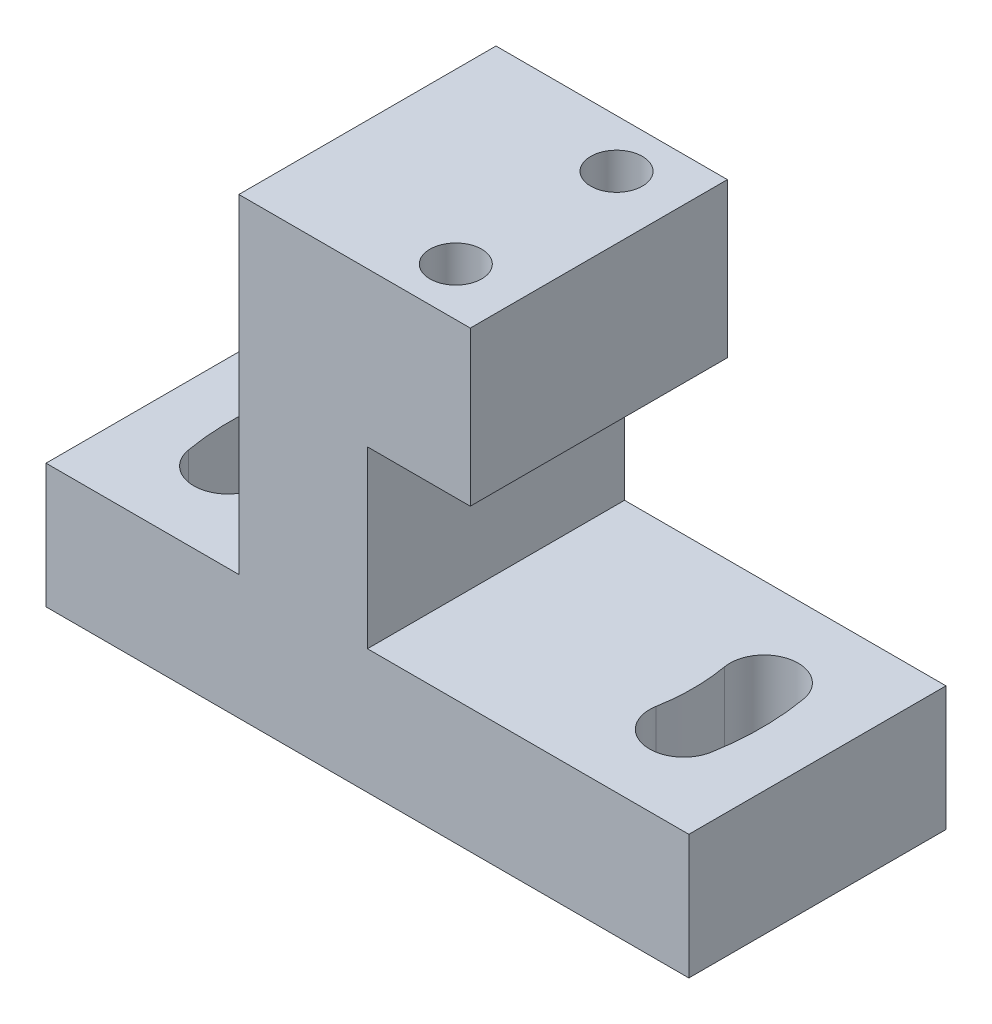
SolidWorks part; units mm, degrees
material "6061 Alloy"
ref_plane "Front Plane" through (0, 0, 0) normal (0, 0, 1) x (1, 0, 0)
ref_plane "Top Plane" through (0, 0, 0) normal (0, 1, 0) x (1, 0, 0)
ref_plane "Right Plane" through (0, 0, 0) normal (1, 0, 0) x (0, 0, -1)
sketch "Sketch1" plane through (0, 0, 0) normal (0, 0, 1) x (1, 0, 0)
  line L2 (-12.7, 44.8056) -> (10.16, 44.8056)
  line L3 (-31.75, 0) -> (31.75, 0)
  line L4 (-31.75, 0) -> (-31.75, 12.2936)
  line L5 (-31.75, 12.2936) -> (-12.7, 12.2936)
  line L6 (31.75, 0) -> (31.75, 12.2936)
  line L8 (-12.7, 12.2936) -> (-12.7, 44.8056)
  line L11 (12.7, 12.2936) -> (31.75, 12.2936)
  line L13 (10.16, 29.5656) -> (0, 29.5656)
  line L14 (10.16, 44.8056) -> (10.16, 29.5656)
  line L15 (12.7, 12.2936) -> (0, 12.2936)
  line L16 (0, 29.5656) -> (0, 12.2936)
  dimension "D1" = 12.7
  dimension "D3" = 63.5
  dimension "D5" = 12.2936
  dimension "D6" = 17.272
  dimension "D7" = 15.24
  dimension "D8" = 10.16
extrude "Extrude1" add sketch "Sketch1" along normal mid plane 25.4
sketch "Sketch2" plane through (0, 12.2936, 0) normal (0, 1, 0) x (-1, 0, 0)
  line L0 (-22.5127, 3.9696) -> (0, 0) construction
  line L1 (0, 0) -> (-22.5127, -3.9696) construction
  line L2 (0, 0) -> (-22.86, 0) construction
  line L3 (0, 22.86) -> (0, -22.86) construction
  circle A0 centre (-22.86, 0) radius 3.3782 construction
  circle A1 centre (0, 0) radius 22.86 construction
  arc A3 (-25.8396, -4.5562) -> (-19.1858, -3.383) centre (-22.5127, -3.9696) ccw
  arc A4 (-19.1858, 3.383) -> (-25.8396, 4.5562) centre (-22.5127, 3.9696) ccw
  arc A5 (-19.1858, 3.383) -> (-19.1858, -3.383) centre (0, 0) ccw
  arc A6 (-25.8396, 4.5562) -> (-25.8396, -4.5562) centre (0, 0) ccw
  dimension "D2" = 45.72
  dimension "D1" = 6.7564
  dimension "D3" = 20
extrude "Arc mounting slot I" cut sketch "Sketch2" against normal through all
mirror "Arc mounting slot II" about plane through (0, 0, 0) normal (1, 0, 0) of "Arc mounting slot I"
hole_wizard "Clamping screw holes" positions "Sketch5" profile "Sketch4" tap size "1/4-20" standard "Ansi Inch"
sketch "Sketch5" plane through (0, 44.8056, 0) normal (0, 1, 0) x (-1, 0, 0)
  line L0 (0, 0) -> (-3.9688, 0) construction
  line L1 (-3.9688, 7.9375) -> (-3.9688, -7.9375) construction
  point P0 (-3.9688, -7.9375)
  point P1 (-3.9688, 7.9375)
  dimension "D1" = 15.875
  dimension "D2" = 3.9688
cosmetic thread "Hole Thread1" parameters "D1"=15.24, "D2"=6.35
cosmetic thread "Hole Thread2" parameters "D1"=15.24, "D2"=6.35
sketch "Sketch4" plane through (3.9688, 44.8056, -7.9375) normal (1, 0, 0) x (0, 0, 1)
  line L0 (0, 0) -> (0, 16.7738)
  line L1 (0, 16.7738) -> (2.5527, 15.24)
  line L2 (2.5527, 15.24) -> (2.5527, 0)
  line L5 (2.5527, 0) -> (0, 0)
  line L10 (0, 16.7738) -> (-2.5527, 15.24) construction
  line L11 (0, -6.35) -> (0, 107.95) construction
  dimension "Tap Drill Dia." = 5.1054
  dimension "Tap Drill Depth" = 15.24
  dimension "Drill Angle" = 118
sketch "Sketch6" plane through (0, 0, 0) normal (0, 0, 1) x (1, 0, 0)
  line L0 (31.75, 0) -> (31.75, 20.2413) construction
  line L3 (7.9375, 20.2311) -> (0, 20.2311)
  line L4 (7.9375, 20.2311) -> (7.9375, 12.2936)
  line L5 (7.9375, 12.2936) -> (0, 12.2936)
  line L6 (0, 20.2311) -> (0, 12.2936)
  dimension "D1" = 20.2413
  dimension "D2" = 7.9375
